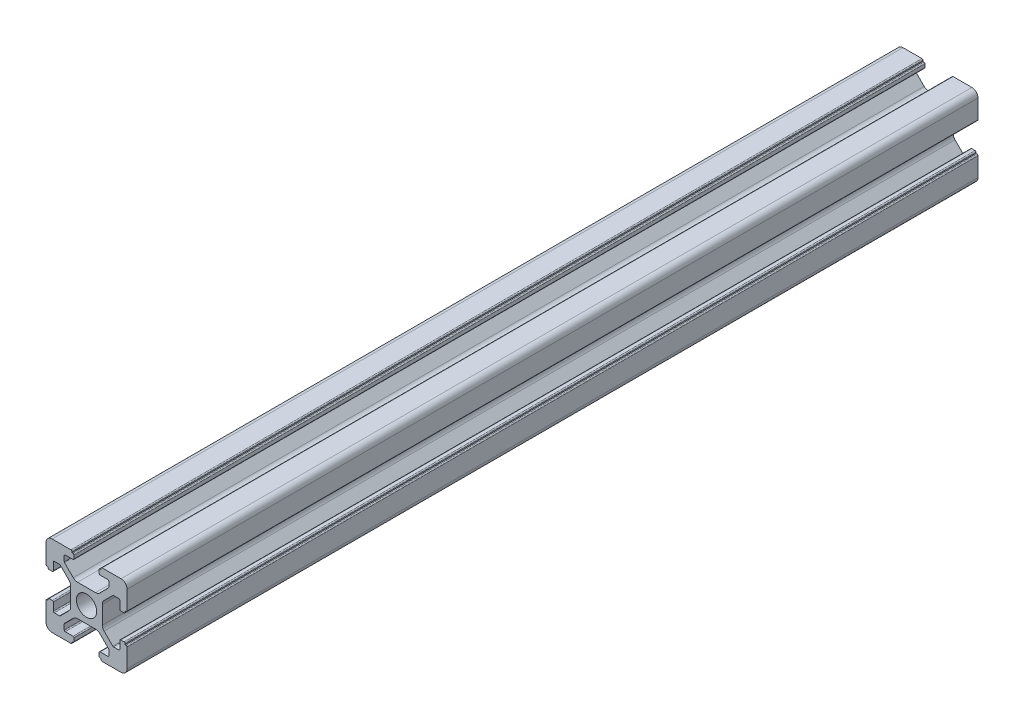
SolidWorks part; units mm, degrees
ref_plane "前视基准面" through (0, 0, 0) normal (0, 0, 1) x (1, 0, 0)
ref_plane "上视基准面" through (0, 0, 0) normal (0, 1, 0) x (1, 0, 0)
ref_plane "右视基准面" through (0, 0, 0) normal (1, 0, 0) x (0, 0, -1)
sketch "草图1" plane through (0, 0, 0) normal (0, 0, 1) x (1, 0, 0)
  line L0 (0, 0) -> (0, 5.5) construction
  line L1 (-8.5023, -10.0023) -> (-3.85, -10.0023)
  line L2 (-10.0023, -8.5023) -> (-10.0023, -3.85)
  line L3 (-8.5023, 10.0023) -> (-3.85, 10.0023)
  line L4 (10.0023, -8.5023) -> (10.0023, -3.85)
  line L5 (-10.0023, -10.0023) -> (10.0023, 10.0023) construction
  line L6 (-10.0023, 10.0023) -> (10.0023, -10.0023) construction
  line L7 (-2.218, -3.9) -> (2.218, -3.9)
  line L8 (-3.9, -2.218) -> (-3.9, 2.218)
  line L9 (-2.218, 3.9) -> (2.218, 3.9)
  line L10 (3.9, -2.218) -> (3.9, 2.218)
  line L11 (-3.9, -3.9) -> (3.9, 3.9) construction
  line L12 (-3.9, 3.9) -> (3.9, -3.9) construction
  line L13 (-5.25, -8.2) -> (-3.35, -8.2)
  line L14 (-8.2, -5.25) -> (-8.2, -3.35)
  line L15 (-5.25, 8.2) -> (-3.35, 8.2)
  line L16 (8.2, -5.25) -> (8.2, -3.35)
  line L17 (-8.2, -8.2) -> (8.2, 8.2) construction
  line L18 (-8.2, 8.2) -> (8.2, -8.2) construction
  line L19 (-7.95, 5.5) -> (-6.6642, 5.5)
  line L20 (0, 0) -> (5.5, 0) construction
  line L23 (-5.5, 7.95) -> (-5.5, 6.6642)
  line L26 (0, 0) -> (-0.5303, 0.5303)
  line L27 (3.2787, 4.3393) -> (5.4268, 6.4874)
  line L28 (0, 0) -> (0.5303, -0.5303)
  line L29 (5.5, 6.6642) -> (5.5, 7.95)
  line L30 (4.3393, 3.2787) -> (6.4874, 5.4268)
  line L31 (6.6642, 5.5) -> (7.95, 5.5)
  line L32 (4.3393, -3.2787) -> (6.4874, -5.4268)
  line L33 (3.2787, -4.3393) -> (5.4268, -6.4874)
  line L34 (-3.2787, -4.3393) -> (-5.4268, -6.4874)
  line L35 (-4.3393, -3.2787) -> (-6.4874, -5.4268)
  line L36 (-4.3393, 3.2787) -> (-6.4874, 5.4268)
  line L37 (-3.2787, 4.3393) -> (-5.4268, 6.4874)
  line L38 (3.1, -8.45) -> (3.1, -9.2523)
  line L39 (8.45, 3.1) -> (9.2523, 3.1)
  line L40 (-5.5, -6.6642) -> (-5.5, -7.95)
  line L41 (-6.6642, -5.5) -> (-7.95, -5.5)
  line L42 (5.5, -6.6642) -> (5.5, -7.95)
  line L43 (6.6642, -5.5) -> (7.95, -5.5)
  line L44 (9.2523, -3.1) -> (8.45, -3.1)
  line L46 (10.0023, 3.85) -> (10.0023, 8.5023)
  line L47 (8.2, 3.35) -> (8.2, 5.25)
  line L48 (-3.1, -9.2523) -> (-3.1, -8.45)
  line L49 (-8.45, -3.1) -> (-9.2523, -3.1)
  line L50 (-9.2523, 3.1) -> (-8.45, 3.1)
  line L51 (-3.1, 8.45) -> (-3.1, 9.2523)
  line L52 (3.1, 9.2523) -> (3.1, 8.45)
  line L53 (3.85, 10.0023) -> (8.5023, 10.0023)
  line L54 (3.35, 8.2) -> (5.25, 8.2)
  line L55 (-10.0023, 3.85) -> (-10.0023, 8.5023)
  line L56 (-8.2, 3.35) -> (-8.2, 5.25)
  line L57 (3.35, -8.2) -> (5.25, -8.2)
  line L58 (3.85, -10.0023) -> (8.5023, -10.0023)
  line L59 (9.7523, -3.6) -> (9.5023, -3.6)
  line L61 (9.7523, 3.6) -> (9.5023, 3.6)
  line L62 (9.5023, -3.6) -> (9.5023, -3.35)
  line L63 (3.6, -9.7523) -> (3.6, -9.5023)
  line L64 (3.35, -9.5023) -> (3.6, -9.5023)
  line L65 (9.5023, 3.35) -> (9.5023, 3.6)
  line L66 (-3.6, -9.5023) -> (-3.35, -9.5023)
  line L67 (-3.6, -9.7523) -> (-3.6, -9.5023)
  line L68 (-9.7523, -3.6) -> (-9.5023, -3.6)
  line L69 (-9.5023, -3.35) -> (-9.5023, -3.6)
  line L70 (-9.5023, 3.6) -> (-9.5023, 3.35)
  line L71 (-9.7523, 3.6) -> (-9.5023, 3.6)
  line L72 (-3.6, 9.7523) -> (-3.6, 9.5023)
  line L73 (-3.35, 9.5023) -> (-3.6, 9.5023)
  line L74 (3.6, 9.5023) -> (3.35, 9.5023)
  line L75 (3.6, 9.7523) -> (3.6, 9.5023)
  circle A0 centre (0, 0) radius 2.5
  arc A1 (10.0023, 8.5023) -> (8.5023, 10.0023) centre (8.5023, 8.5023) ccw
  arc A2 (8.5023, -10.0023) -> (10.0023, -8.5023) centre (8.5023, -8.5023) ccw
  arc A3 (-10.0023, -8.5023) -> (-8.5023, -10.0023) centre (-8.5023, -8.5023) ccw
  arc A4 (-10.0023, 8.5023) -> (-8.5023, 10.0023) centre (-8.5023, 8.5023) cw
  arc A5 (-9.5023, -3.35) -> (-9.2523, -3.1) centre (-9.2523, -3.35) cw
  arc A6 (-9.7523, -3.6) -> (-10.0023, -3.85) centre (-9.7523, -3.85) ccw
  arc A7 (-8.45, -3.1) -> (-8.2, -3.35) centre (-8.45, -3.35) cw
  arc A8 (-7.95, -5.5) -> (-8.2, -5.25) centre (-7.95, -5.25) cw
  arc A9 (-6.4874, -5.4268) -> (-6.6642, -5.5) centre (-6.6642, -5.25) cw
  arc A10 (-5.4268, -6.4874) -> (-5.5, -6.6642) centre (-5.25, -6.6642) ccw
  arc A11 (-5.5, -7.95) -> (-5.25, -8.2) centre (-5.25, -7.95) ccw
  arc A12 (-3.6, -9.7523) -> (-3.85, -10.0023) centre (-3.85, -9.7523) cw
  arc A13 (-3.35, -9.5023) -> (-3.1, -9.2523) centre (-3.35, -9.2523) ccw
  arc A14 (-3.1, -8.45) -> (-3.35, -8.2) centre (-3.35, -8.45) ccw
  arc A15 (3.1, -8.45) -> (3.35, -8.2) centre (3.35, -8.45) cw
  arc A16 (5.5, -7.95) -> (5.25, -8.2) centre (5.25, -7.95) cw
  arc A17 (5.4268, -6.4874) -> (5.5, -6.6642) centre (5.25, -6.6642) cw
  arc A18 (6.4874, -5.4268) -> (6.6642, -5.5) centre (6.6642, -5.25) ccw
  arc A19 (7.95, -5.5) -> (8.2, -5.25) centre (7.95, -5.25) ccw
  arc A20 (8.45, -3.1) -> (8.2, -3.35) centre (8.45, -3.35) ccw
  arc A21 (9.5023, -3.35) -> (9.2523, -3.1) centre (9.2523, -3.35) ccw
  arc A22 (9.7523, -3.6) -> (10.0023, -3.85) centre (9.7523, -3.85) cw
  arc A23 (3.35, -9.5023) -> (3.1, -9.2523) centre (3.35, -9.2523) cw
  arc A24 (3.6, -9.7523) -> (3.85, -10.0023) centre (3.85, -9.7523) ccw
  arc A25 (7.95, 5.5) -> (8.2, 5.25) centre (7.95, 5.25) cw
  arc A26 (8.2, 3.35) -> (8.45, 3.1) centre (8.45, 3.35) ccw
  arc A27 (9.5023, 3.35) -> (9.2523, 3.1) centre (9.2523, 3.35) cw
  arc A28 (9.7523, 3.6) -> (10.0023, 3.85) centre (9.7523, 3.85) ccw
  arc A29 (6.6642, 5.5) -> (6.4874, 5.4268) centre (6.6642, 5.25) ccw
  arc A30 (5.4268, 6.4874) -> (5.5, 6.6642) centre (5.25, 6.6642) ccw
  arc A31 (5.5, 7.95) -> (5.25, 8.2) centre (5.25, 7.95) ccw
  arc A32 (3.1, 8.45) -> (3.35, 8.2) centre (3.35, 8.45) ccw
  arc A33 (3.6, 9.7523) -> (3.85, 10.0023) centre (3.85, 9.7523) cw
  arc A34 (3.35, 9.5023) -> (3.1, 9.2523) centre (3.35, 9.2523) ccw
  arc A35 (-9.7523, 3.6) -> (-10.0023, 3.85) centre (-9.7523, 3.85) cw
  arc A36 (-9.5023, 3.35) -> (-9.2523, 3.1) centre (-9.2523, 3.35) ccw
  arc A37 (-8.45, 3.1) -> (-8.2, 3.35) centre (-8.45, 3.35) ccw
  arc A38 (-8.2, 5.25) -> (-7.95, 5.5) centre (-7.95, 5.25) cw
  arc A39 (-6.4874, 5.4268) -> (-6.6642, 5.5) centre (-6.6642, 5.25) ccw
  arc A40 (-5.4268, 6.4874) -> (-5.5, 6.6642) centre (-5.25, 6.6642) cw
  arc A41 (-5.5, 7.95) -> (-5.25, 8.2) centre (-5.25, 7.95) cw
  arc A42 (-3.1, 8.45) -> (-3.35, 8.2) centre (-3.35, 8.45) cw
  arc A43 (-3.1, 9.2523) -> (-3.35, 9.5023) centre (-3.35, 9.2523) ccw
  arc A44 (-3.6, 9.7523) -> (-3.85, 10.0023) centre (-3.85, 9.7523) ccw
  arc A45 (-4.3393, 3.2787) -> (-3.9, 2.218) centre (-5.4, 2.218) cw
  arc A46 (-3.2787, 4.3393) -> (-2.218, 3.9) centre (-2.218, 5.4) ccw
  arc A47 (3.2787, 4.3393) -> (2.218, 3.9) centre (2.218, 5.4) cw
  arc A48 (4.3393, 3.2787) -> (3.9, 2.218) centre (5.4, 2.218) ccw
  arc A49 (4.3393, -3.2787) -> (3.9, -2.218) centre (5.4, -2.218) cw
  arc A50 (3.2787, -4.3393) -> (2.218, -3.9) centre (2.218, -5.4) ccw
  arc A51 (-4.3393, -3.2787) -> (-3.9, -2.218) centre (-5.4, -2.218) ccw
  arc A52 (-2.218, -3.9) -> (-3.2787, -4.3393) centre (-2.218, -5.4) ccw
  point P0 (0, 0)
  point P7 (10.0023, 0)
  point P62 (0, 0)
  point P76 (0, 0)
  point P92 (-8.2, -5.5)
  point P99 (0, 0)
  point P106 (-5.5, -8.2)
  point P117 (5.5, -8.2)
  point P124 (8.2, -5.5)
  point P137 (8.2, 5.5)
  point P140 (8.2, 3.1)
  point P147 (6.5607, 5.5)
  point P152 (5.5, 8.2)
  point P167 (-8.2, 5.5)
  point P174 (-5.5, 8.2)
  dimension "D1" = 1.5
  dimension "D5" = 0.25
  dimension "D6" = 1.5
  dimension "D2" = 4
  dimension "D3" = 4
  dimension "D4" = 4
extrude "凸台-拉伸1" add sketch "草图1" along normal blind 210 contours A52 L7 A50 L33 A17 L42 A16 L57 A15 L38 A23 L64 L63 A24 L58 A2 L4 A22 L59 L62 A21 L44 A20 L16 A19 L43 A18 L32 A49 L10 A48 L30 A29 L31 A25 L47 A26 L39 A27 L65 L61 A28 L46 A1 L53 A33 L75 L74 A34 L52 A32
